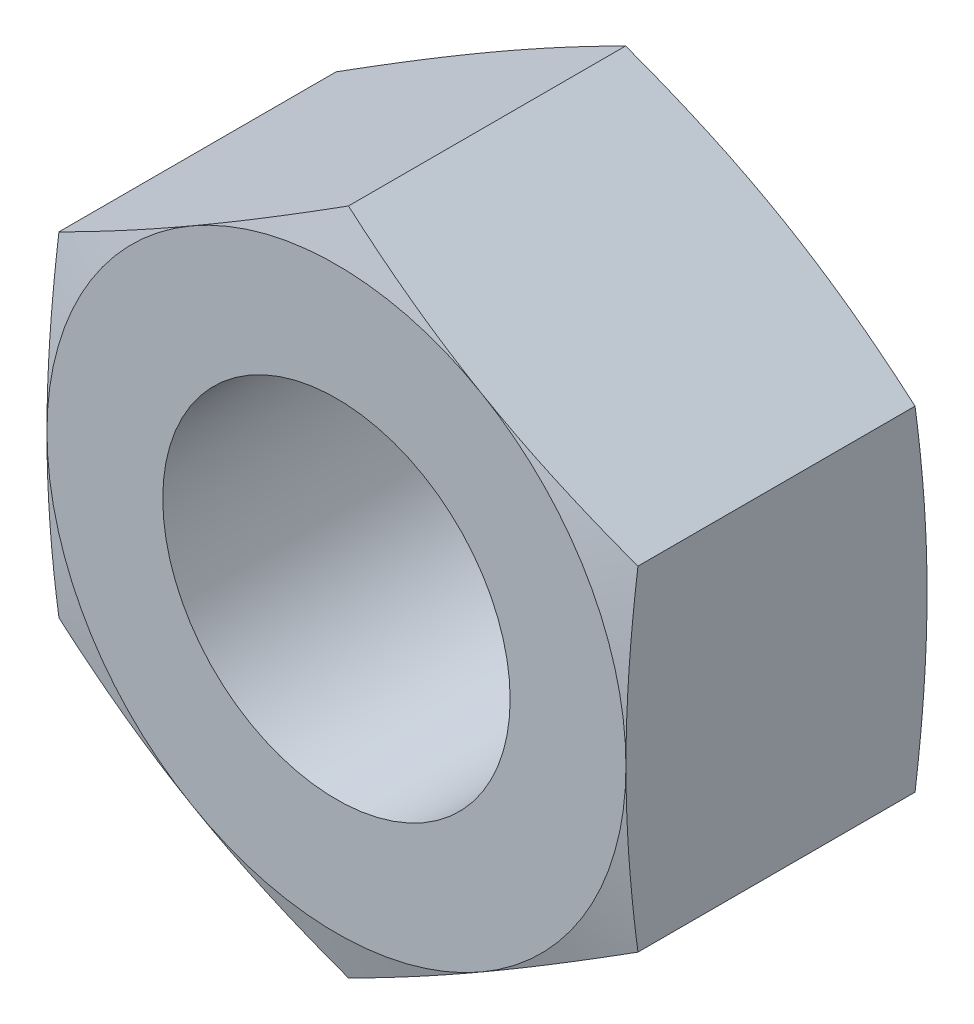
SolidWorks part; units mm, degrees
ref_plane "Front" through (0, 0, 0) normal (0, 0, 1) x (1, 0, 0)
ref_plane "Top" through (0, 0, 0) normal (0, 1, 0) x (1, 0, 0)
ref_plane "Right" through (0, 0, 0) normal (1, 0, 0) x (0, 0, -1)
sketch "Sketch1" plane through (0, 0, 0) normal (0, 0, 1) x (1, 0, 0)
  line L1 (0, 5.7735) -> (-5, 2.8868)
  line L2 (-5, 2.8868) -> (-5, -2.8868)
  line L3 (-5, -2.8868) -> (0, -5.7735)
  line L4 (0, -5.7735) -> (5, -2.8868)
  line L5 (5, -2.8868) -> (5, 2.8868)
  line L6 (5, 2.8868) -> (0, 5.7735)
  circle A0 centre (0, 0) radius 5 construction
  circle A1 centre (0, 0) radius 3
  dimension "D1" = 10
  dimension "D2" = 6
extrude "Boss-Extrude1" add sketch "Sketch1" along normal blind 5.2
sketch "Sketch2" plane through (0, 0, 0) normal (0, 1, 0) x (0, 0, -1)
  line L0 (-4.3962, -8) -> (-6.4058, -0.5)
  line L3 (-6.4058, -0.5) -> (-6.4058, -8)
  line L4 (-6.4058, -8) -> (-4.3962, -8)
  dimension "D1" = 15
  dimension "D2" = 0.5
  dimension "D3" = 8
sketch "Sketch3" plane through (0, 0, 0) normal (1, 0, 0) x (0, 0, -1)
  line L0 (2.8088, 0) -> (-4.7656, 0) construction
revolve "Cut-Revolve2" cut sketch "Sketch2" angle 360 about L0
ref_plane "Plane1" through (0, 0, 2.6) normal (0, 0, 1) x (1, 0, 0)
mirror "Mirror1" about plane through (0, 0, 2.6) normal (0, 0, 1) of "Cut-Revolve2"
